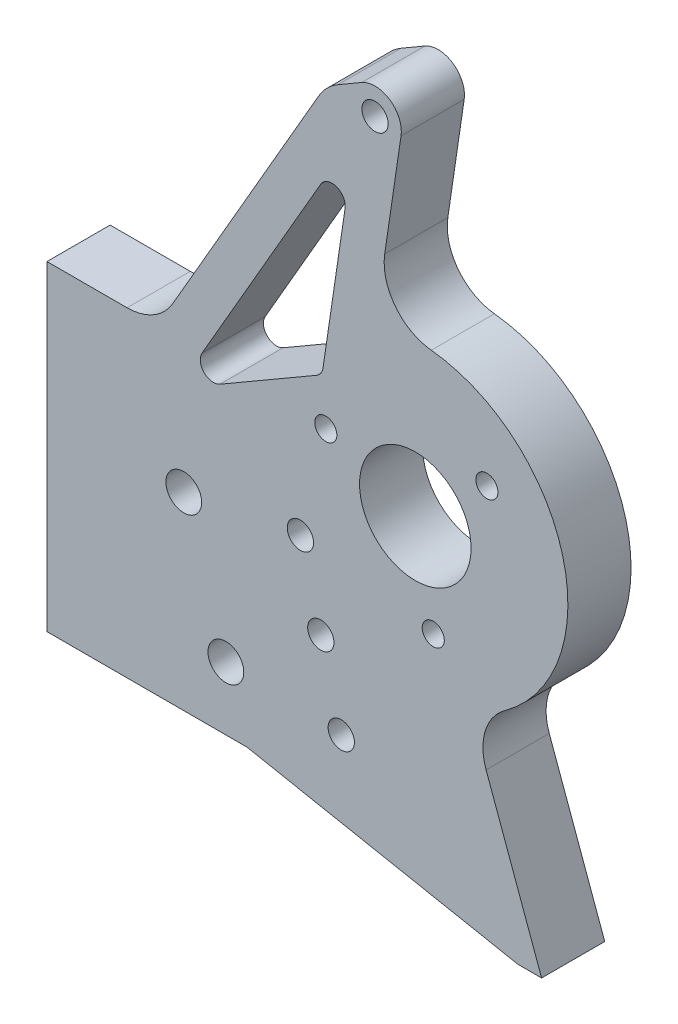
SolidWorks part; units mm, degrees
material "7075-T6, Chapa (SS)"
ref_plane "Plano frontal" through (0, 0, 0) normal (0, 0, 1) x (1, 0, 0)
ref_plane "Plano superior" through (0, 0, 0) normal (0, 1, 0) x (1, 0, 0)
ref_plane "Plano direito" through (0, 0, 0) normal (1, 0, 0) x (0, 0, -1)
sketch "Esboço1" plane through (0, 0, 0) normal (0, 0, 1) x (1, 0, 0)
  line L1 (0, 0) -> (36, 0)
  line L2 (36, 0) -> (36, -10)
  line L3 (36, -10) -> (94, -10)
  line L8 (94, -10) -> (80.5393, 26.9829)
  line L24 (0, 60.92) -> (21, 60.92)
  line L26 (62.3723, 81.9789) -> (68.8, 125.5069)
  line L27 (68.8, 125.5069) -> (53, 116.3456)
  line L31 (53, 116.3456) -> (21, 60.92)
  line L32 (0, 60.92) -> (0, 0)
  circle A1 centre (70, 54) radius 10.6
  circle A2 centre (70, 54) radius 66 construction
  arc A5 (80.5393, 26.9829) -> (62.3723, 81.9789) centre (70, 54) ccw
  dimension "D4" = 132
  dimension "D5" = 21.2
  dimension "D13" = 29
  dimension "D16" = 15.8
  dimension "D6" = 44
  dimension "D2" = 21
  dimension "D3" = 10
  dimension "D7" = 60.92
  dimension "D8" = 70
  dimension "D9" = 54
  dimension "D10" = 70
  dimension "D11" = 36
  dimension "D12" = 94
  dimension "D14" = 64
  dimension "D15" = 60
  dimension "D17" = 21.6
extrude "Ressalto-extrusão1" add sketch "Esboço1" along normal blind 12
fillet "Filete1" radius 10 3 edges at (53, 116.3456, 6) (21, 60.92, 6) (62.3723, 81.9789, 6)
sketch "Esboço2" plane through (0, 0, 12) normal (0, 0, 1) x (1, 0, 0)
  line L0 (24.7834, 52.473) -> (58.5701, 110.9933)
  line L4 (58.5701, 110.9933) -> (52.2834, 68.42)
  line L5 (52.2834, 68.42) -> (24.7834, 52.473)
  line L6 (64.184, 94.2472) -> (68.8, 125.5069) construction
  line L7 (51.6652, 114.0337) -> (23.8868, 65.92) construction
  line L8 (15.2265, 60.92) -> (0, 60.92) construction
  dimension "D1" = 7.5
  dimension "D2" = 8
  dimension "D3" = 27.5
  dimension "D4" = 7.5
extrude "Corte-extrusão1" cut sketch "Esboço2" against normal through all
sketch "Esboço6" plane through (0, 0, 12) normal (0, 0, 1) x (1, 0, 0)
  circle A0 centre (70, 54) radius 66 construction
  dimension "D1" = 132
fillet "Filete3" radius 2.5 3 edges at (58.5701, 110.9933, 6) (52.2834, 68.42, 6) (24.7834, 52.473, 6)
sketch "Esboço8" plane through (0, 0, 12) normal (0, 0, 1) x (1, 0, 0)
  line L1 (36, -10) -> (94, -10) construction
  line L2 (89.5, -10) -> (38, 0)
  line L4 (36, -10) -> (89.5, -10)
  line L5 (38, 0) -> (36, 0)
  line L6 (36, 0) -> (36, -10)
  dimension "D1" = 53.5
  dimension "D2" = 2
extrude "Corte-extrusão2" cut sketch "Esboço8" against normal through all
hole_wizard "Broca de rosquear para tarraxa de M81" positions "Esboço9" profile "Esboço10" hole size "M8" standard "ISO"
sketch "Esboço9" plane through (0, 0, 0) normal (-1, 0, 0) x (0, 0, 1)
  line L0 (6, 60.92) -> (6, 0) construction
  line L1 (12, 60.92) -> (0, 60.92) construction
  line L2 (12, 0) -> (0, 0) construction
  point P0 (6, 50.92)
  point P2 (6, 30.46)
  point P4 (6, 10)
  dimension "D1" = 10
  dimension "D2" = 10
sketch "Esboço10" plane through (0, 50.92, 6) normal (0, 1, 0) x (0, 0, 1)
  line L0 (0, 0) -> (0, 17.0429)
  line L1 (0, 17.0429) -> (3.4, 15)
  line L2 (3.4, 15) -> (3.4, 0)
  line L5 (3.4, 0) -> (0, 0)
  line L10 (0, 17.0429) -> (-3.4, 15) construction
  line L11 (0, -6.35) -> (0, 107.95) construction
  dimension "Hole Dia." = 6.8
  dimension "Hole Depth" = 15
  dimension "Drill Angle" = 118
fillet "Filete6" radius 10 1 edges at (80.5393, 26.9829, 6)
fillet "Filete7" radius 5 1 edges at (68.8, 125.5069, 6)
hole_wizard "Broca de rosquear para tarraxa de M61" positions "Esboço11" profile "Esboço12" hole size "M6" standard "ISO" end condition through all
sketch "Esboço11" plane through (0, 0, 12) normal (0, 0, 1) x (1, 0, 0)
  line L0 (48.1614, 39.9522) -> (55.926, 10.9744) construction
  line L1 (0, 60.92) -> (0, 0) construction
  line L2 (15.2265, 60.92) -> (0, 60.92) construction
  line L3 (0, 0) -> (38, 0) construction
  point P0 (48.1614, 39.9522)
  point P3 (52.0437, 25.4633)
  point P6 (55.926, 10.9744)
  dimension "D1" = 48.1614
  dimension "D2" = 15
  dimension "D3" = 15
  dimension "D4" = 20.9678
  dimension "D5" = 75
sketch "Esboço12" plane through (48.1614, 39.9522, 12) normal (1, 0, 0) x (0, -1, 0)
  line L0 (0, 0) -> (0, 12)
  line L1 (0, 12) -> (2.5, 12)
  line L2 (2.5, 12) -> (2.5, 0)
  line L5 (2.5, 0) -> (0, 0)
  line L11 (0, -6.35) -> (0, 107.95) construction
  dimension "Thru Hole Dia." = 5
  dimension "Thru Hole Depth" = 12
hole_wizard "Broca de rosquear para tarraxa de M82" positions "Esboço13" profile "Esboço14" hole size "M8" standard "ISO" end condition through all
sketch "Esboço13" plane through (0, 0, 12) normal (0, 0, 1) x (1, 0, 0)
  line L1 (0, 60.92) -> (0, 0) construction
  line L2 (15.2265, 60.92) -> (0, 60.92) construction
  line L3 (0, 0) -> (38, 0) construction
  point P0 (26, 35.9522)
  point P3 (34, 12)
  dimension "D1" = 26
  dimension "D2" = 24.9678
  dimension "D3" = 12
  dimension "D4" = 34
sketch "Esboço14" plane through (26, 35.9522, 12) normal (1, 0, 0) x (0, -1, 0)
  line L0 (0, 0) -> (0, 12)
  line L1 (0, 12) -> (3.4, 12)
  line L2 (3.4, 12) -> (3.4, 0)
  line L5 (3.4, 0) -> (0, 0)
  line L11 (0, -6.35) -> (0, 107.95) construction
  dimension "Thru Hole Dia." = 6.8
  dimension "Thru Hole Depth" = 12
hole_wizard "Broca de rosquear para tarraxa de M51" positions "Esboço17" profile "Esboço18" hole size "M5" standard "ISO" end condition through all
sketch "Esboço17" plane through (0, 0, 12) normal (0, 0, 1) x (1, 0, 0)
  circle A0 centre (70, 54) radius 18 construction
  point P0 (83.6009, 65.7905)
  point P3 (73.4104, 36.326)
  point P6 (52.9887, 59.8835)
  dimension "D1" = 36
  dimension "D2" = 5.8835
  dimension "D3" = 10.1905
  dimension "D4" = 17.674
sketch "Esboço18" plane through (83.6009, 65.7905, 12) normal (1, 0, 0) x (0, -1, 0)
  line L0 (0, 0) -> (0, 12)
  line L1 (0, 12) -> (2.1, 12)
  line L2 (2.1, 12) -> (2.1, 0)
  line L5 (2.1, 0) -> (0, 0)
  line L11 (0, -6.35) -> (0, 107.95) construction
  dimension "Thru Hole Dia." = 4.2
  dimension "Thru Hole Depth" = 12
hole_wizard "Broca de rosquear para tarraxa de M62" positions "Esboço19" profile "Esboço20" hole size "M6" standard "ISO" end condition through all
sketch "Esboço19" plane through (0, 0, 12) normal (0, 0, 1) x (1, 0, 0)
  line L0 (59.8311, 120.3065) -> (55.3094, 117.6847) construction
  line L1 (64.184, 94.2472) -> (67.2855, 115.2506) construction
  point P0 (62.3391, 115.981)
  dimension "D1" = 5
  dimension "D2" = 5
sketch "Esboço20" plane through (62.3391, 115.981, 12) normal (1, 0, 0) x (0, -1, 0)
  line L0 (0, 0) -> (0, 12)
  line L1 (0, 12) -> (2.5, 12)
  line L2 (2.5, 12) -> (2.5, 0)
  line L5 (2.5, 0) -> (0, 0)
  line L11 (0, -6.35) -> (0, 107.95) construction
  dimension "Thru Hole Dia." = 5
  dimension "Thru Hole Depth" = 12
